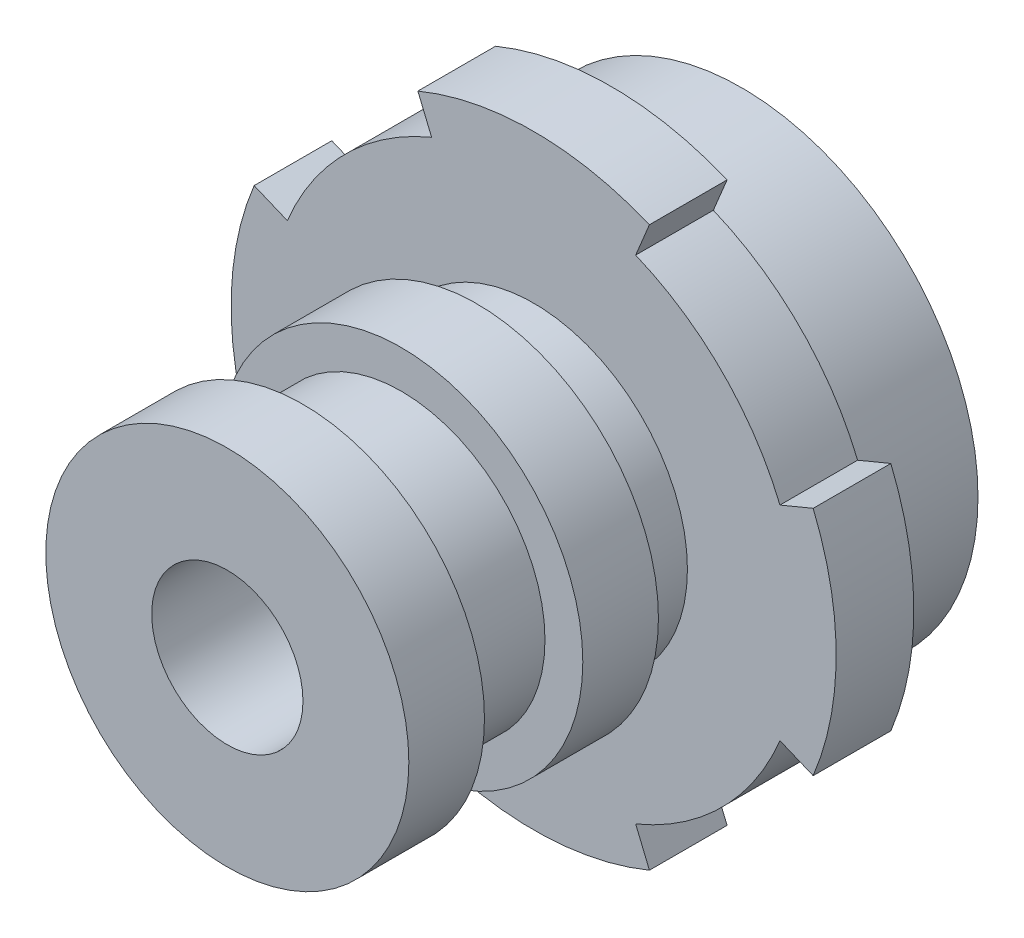
SolidWorks part; units mm, degrees
ref_plane "Piano frontale" through (0, 0, 0) normal (0, 0, 1) x (1, 0, 0)
ref_plane "Piano superiore" through (0, 0, 0) normal (0, 1, 0) x (1, 0, 0)
ref_plane "Piano destro" through (0, 0, 0) normal (1, 0, 0) x (0, 0, -1)
sketch "Schizzo1" plane through (0, 0, 0) normal (1, 0, 0) x (0, 0, -1)
  line L0 (-49.0256, 0) -> (62.359, 0) construction
  line L1 (-40.8205, 20) -> (65.1795, 20)
  line L2 (65.1795, 20) -> (65.1795, 48)
  line L3 (65.1795, 48) -> (95.1795, 48)
  line L4 (95.1795, 48) -> (95.1795, 62.5)
  line L5 (95.1795, 62.5) -> (60.7179, 62.5)
  line L6 (60.7179, 62.5) -> (60.7179, 80)
  line L7 (60.7179, 80) -> (40.1795, 80)
  line L8 (40.1795, 80) -> (40.1795, 40.6667)
  line L9 (40.1795, 40.6667) -> (25.1795, 40.6667)
  line L10 (25.1795, 40.6667) -> (25.1795, 48)
  line L11 (25.1795, 48) -> (5.1795, 48)
  line L12 (5.1795, 48) -> (5.1795, 38)
  line L13 (5.1795, 38) -> (-20.8205, 38)
  line L14 (-20.8205, 38) -> (-20.8205, 48)
  line L15 (-20.8205, 48) -> (-40.8205, 48)
  line L16 (-40.8205, 48) -> (-40.8205, 20)
  point P5 (8.6154, 48.6154)
  dimension "D1" = 40
  dimension "D2" = 96
  dimension "D3" = 76
  dimension "D4" = 96
  dimension "D5" = 125
  dimension "D6" = 55
  dimension "D7" = 96
  dimension "D8" = 20
  dimension "D9" = 15
  dimension "D10" = 160
  dimension "D11" = 30
  dimension "D12" = 20
  dimension "D13" = 26
revolve "Rivoluzione1" add sketch "Schizzo1" angle 360 about L0
sketch "Schizzo2" plane through (0, 0, -60.7179) normal (0, 0, -1) x (-1, 0, 0)
  line L0 (0, 95.5371) -> (0, -91.8882) construction
  line L1 (0, 0) -> (103.3236, 0) construction
  line L2 (0, 0) -> (101.1964, 41.9169)
  line L3 (0, 0) -> (38.22, 92.2712)
  circle A2 centre (0, 0) radius 62.5 construction
  circle A3 centre (0, 0) radius 80 construction
  circle A4 centre (0, 0) radius 70.5
  point P5 (0, 70.5)
  point P7 (0, 62.5)
  point P8 (0, 80)
  circle M1 centre (0, 0) radius 80
  dimension "D3" = 17.5
  dimension "D1" = 22.5
  dimension "D2" = 22.5
  dimension "D4" = 8
extrude "Taglio-Estrusione1" cut sketch "Schizzo2" against normal through all contours A4 L2 L3 M1
pattern_circular "RipetizioneCircolare1" count 4 over 360 about axis through (0, 0, 49.0256) along (0, 0, 1) of "Taglio-Estrusione1"
